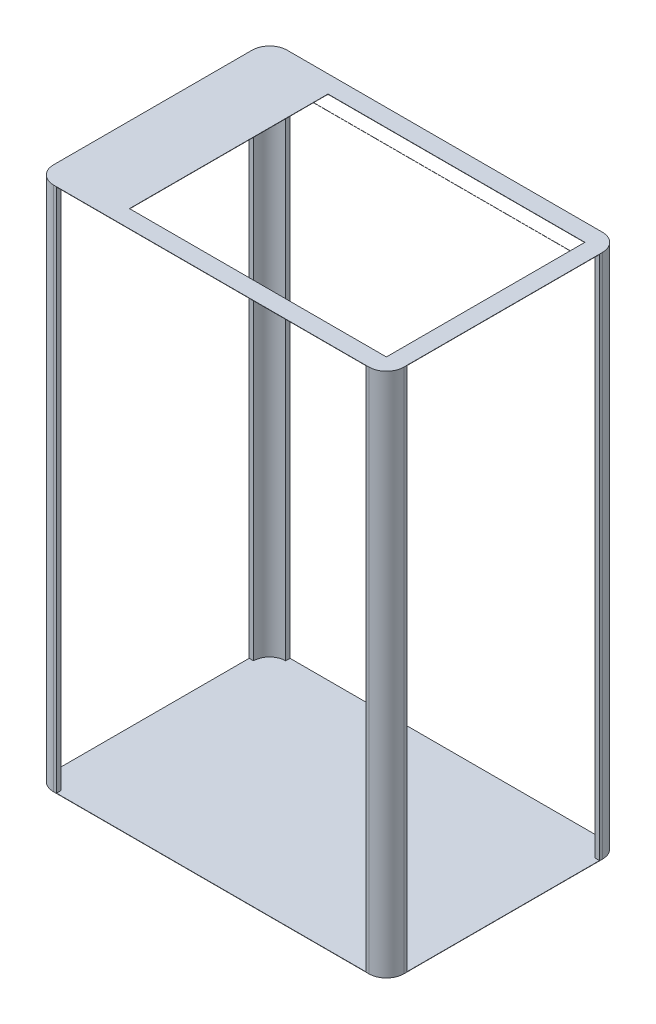
SolidWorks part; units mm, degrees
ref_plane "Front Plane" through (0, 0, 0) normal (0, 0, 1) x (1, 0, 0)
ref_plane "Top Plane" through (0, 0, 0) normal (0, 1, 0) x (1, 0, 0)
ref_plane "Right Plane" through (0, 0, 0) normal (1, 0, 0) x (0, 0, -1)
sketch "Sketch2" plane through (0, 0, 0) normal (0, 1, 0) x (1, 0, 0)
  line L1 (-270, -200) -> (270, -200)
  line L2 (-300, -170) -> (-300, 170)
  line L3 (-270, 200) -> (270, 200)
  line L4 (300, -170) -> (300, 170)
  line L5 (-289.3669, -192.9112) -> (289.3669, 192.9112) construction
  line L6 (-289.3669, 192.9112) -> (289.3669, -192.9112) construction
  arc A0 (-270, 200) -> (-300, 170) centre (-270, 170) ccw
  arc A1 (300, 170) -> (270, 200) centre (270, 170) ccw
  arc A2 (270, -200) -> (300, -170) centre (270, -170) ccw
  arc A3 (-300, -170) -> (-270, -200) centre (-270, -170) ccw
  point P0 (0, 0)
  dimension "D3" = 60
extrude "Boss-Extrude1" add sketch "Sketch2" along normal mid plane 900
sketch "Sketch3" plane through (0, 0, 0) normal (0, 1, 0) x (1, 0, 0)
  line L1 (-265, -200) -> (265, -200)
  line L2 (-300, -165) -> (-300, 165)
  line L3 (-265, 200) -> (265, 200)
  line L4 (300, -165) -> (300, 165)
  line L5 (-281.0238, -187.3492) -> (281.0238, 187.3492) construction
  line L6 (-281.0238, 187.3492) -> (281.0238, -187.3492) construction
  line L7 (-292.5, 165) -> (-300, 165)
  line L8 (-265, 192.5) -> (-265, 200)
  line L9 (265, 192.5) -> (265, 200)
  line L10 (292.5, 165) -> (300, 165)
  line L11 (265, -192.5) -> (265, -200)
  line L12 (292.5, -165) -> (300, -165)
  line L13 (-265, -192.5) -> (-265, -200)
  line L14 (-292.5, -165) -> (-300, -165)
  arc A0 (-265, 192.5) -> (-292.5, 165) centre (-265, 165) ccw
  arc A2 (292.5, 165) -> (265, 192.5) centre (265, 165) ccw
  arc A3 (-292.5, -165) -> (-265, -192.5) centre (-265, -165) ccw
  arc A4 (265, -192.5) -> (292.5, -165) centre (265, -165) ccw
  point P0 (0, 0)
  dimension "D3" = 55
  dimension "D4" = 35
  dimension "D6" = 55
  dimension "D7" = 35
  dimension "D8" = 35
  dimension "D9" = 35
  dimension "D10" = 35
  dimension "D11" = 35
  dimension "D12" = 35
  dimension "D13" = 55
  dimension "D14" = 55
  dimension "D5" = 35
extrude "Cut-Extrude1" cut sketch "Sketch3" against normal mid plane 899
sketch "Sketch4" plane through (0, 450, 0) normal (0, 1, 0) x (1, 0, 0)
  line L5 (270, 200) -> (-270, 200) construction
  line L6 (-270, -200) -> (270, -200) construction
  line L7 (-170, -170) -> (270, -170)
  line L8 (-170, -170) -> (-170, 170)
  line L9 (-170, 170) -> (270, 170)
  line L10 (270, -170) -> (270, 170)
  line L11 (-170, -170) -> (270, 170) construction
  line L12 (-170, 170) -> (270, -170) construction
  line L14 (300, -170) -> (300, 170) construction
  point P0 (-4.3506, 35.3453)
  point P5 (50, 0)
  dimension "D1" = 30
  dimension "D2" = 340
  dimension "D3" = 30
  dimension "D4" = 30
  dimension "D5" = 440
extrude "Cut-Extrude2" cut sketch "Sketch4" against normal blind 10
ref_plane "Plane1" through (300, 450, -170) normal (0, 0, -1) x (-1, 0, 0)
sketch "Sketch7" plane through (300, 0, 0) normal (1, 0, 0) x (0, 0, -1)
  line L0 (165, -449.5) -> (165, 449.5) construction
  line L1 (-165, 449.5) -> (165, 449.5) construction
  circle A0 centre (145, 449.75) radius 0.125
  dimension "D1" = 0.25
  dimension "D2" = 20
  dimension "D3" = 0.25
extrude "Boss-Extrude2" add sketch "Sketch7" against normal up to surface (470 mm away) up to face at (-170, 449.75, 0)
